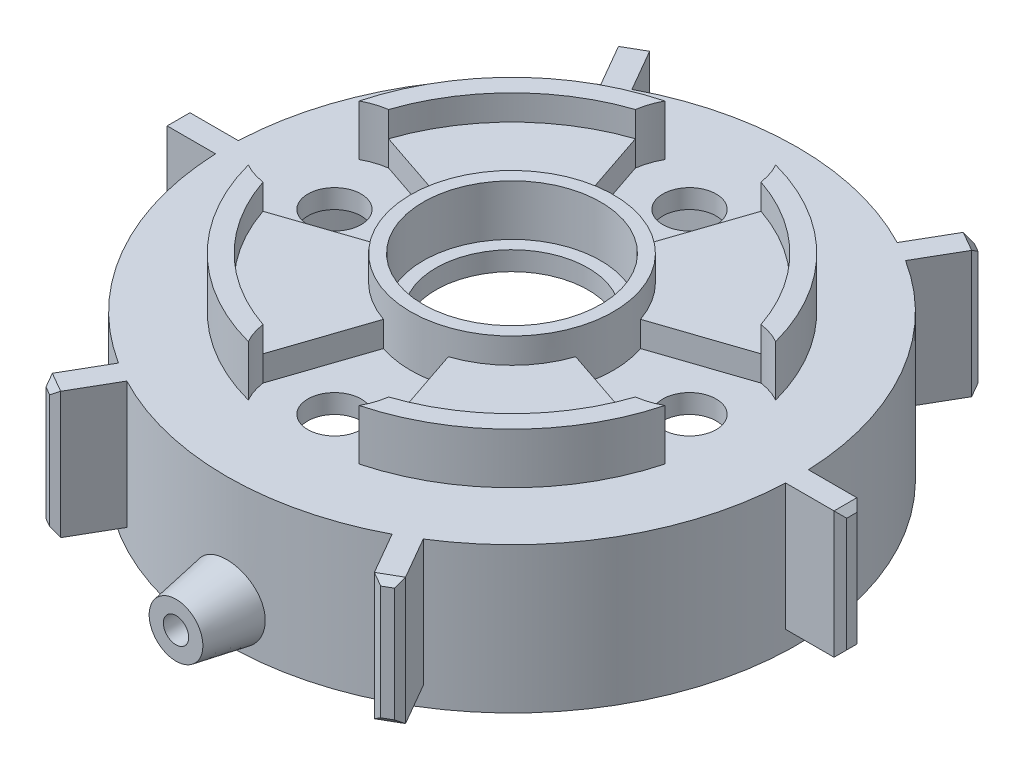
SolidWorks part; units mm, degrees
ref_plane "前视基准面" through (0, 0, 0) normal (0, 0, 1) x (1, 0, 0)
ref_plane "上视基准面" through (0, 0, 0) normal (0, 1, 0) x (1, 0, 0)
ref_plane "右视基准面" through (0, 0, 0) normal (1, 0, 0) x (0, 0, -1)
sketch "草图2" plane through (0, 0, 0) normal (0, 1, 0) x (1, 0, 0)
  line L0 (0, 30.8283) -> (0, -31.2236) construction
  line L1 (-31.2236, 0) -> (33.595, 0) construction
  circle A0 centre (0, 0) radius 22.5
  circle A1 centre (0, 0) radius 14 construction
  circle A2 centre (14, 0) radius 2.1
  circle A3 centre (0, 14) radius 2.1
  circle A4 centre (0, -14) radius 2.1
  circle A5 centre (-14, 0) radius 2.1
  circle A6 centre (0, 0) radius 6
  dimension "D1" = 45
  dimension "D2" = 4.2
  dimension "D3" = 4.2
  dimension "D4" = 28
  dimension "D5" = 12
extrude "凸台-拉伸1" add sketch "草图2" along normal blind 1.5
sketch "草图4" plane through (0, 0, 0) normal (0, -1, 0) x (1, 0, 0)
  circle A1 centre (0, 0) radius 22.5 construction
  circle A2 centre (0, 0) radius 22.5
  circle A3 centre (0, 0) radius 21
  dimension "D1" = 1.5
extrude "凸台-拉伸2" add sketch "草图4" along normal blind 10
sketch "草图5" plane through (0, 1.5, 0) normal (0, 1, 0) x (1, 0, 0)
  line L0 (-22.5, 0) -> (24.7317, 0) construction
  line L1 (0, 22.5) -> (0, -24.6712) construction
  line L2 (26.8, 0.9) -> (26.8, -0.9)
  line L3 (26.8, -0.9) -> (21, -0.9)
  line L4 (21, -0.9) -> (21, 0.9)
  line L5 (26.8, 0.9) -> (21, 0.9)
  line L6 (12.6206, -23.6595) -> (9.7206, -18.6365)
  line L7 (14.1794, -22.7595) -> (12.6206, -23.6595)
  line L8 (14.1794, -22.7595) -> (11.2794, -17.7365)
  line L9 (9.7206, -18.6365) -> (11.2794, -17.7365)
  line L10 (-14.1794, -22.7595) -> (-11.2794, -17.7365)
  line L11 (-12.6206, -23.6595) -> (-14.1794, -22.7595)
  line L12 (-12.6206, -23.6595) -> (-9.7206, -18.6365)
  line L13 (-11.2794, -17.7365) -> (-9.7206, -18.6365)
  line L14 (-26.8, 0.9) -> (-21, 0.9)
  line L15 (-26.8, -0.9) -> (-26.8, 0.9)
  line L16 (-26.8, -0.9) -> (-21, -0.9)
  line L17 (-21, 0.9) -> (-21, -0.9)
  line L18 (-12.6206, 23.6595) -> (-9.7206, 18.6365)
  line L19 (-14.1794, 22.7595) -> (-12.6206, 23.6595)
  line L20 (-14.1794, 22.7595) -> (-11.2794, 17.7365)
  line L21 (-9.7206, 18.6365) -> (-11.2794, 17.7365)
  line L22 (14.1794, 22.7595) -> (11.2794, 17.7365)
  line L23 (12.6206, 23.6595) -> (14.1794, 22.7595)
  line L24 (12.6206, 23.6595) -> (9.7206, 18.6365)
  line L25 (11.2794, 17.7365) -> (9.7206, 18.6365)
  circle A0 centre (0, 0) radius 22.5 construction
  point P14 (21, 0)
  point P15 (26.8, 0)
  dimension "D1" = 1.8
  dimension "D2" = 21
  dimension "D3" = 5.8
  dimension "D4" = 6
extrude "凸台-拉伸3" add sketch "草图5" against normal blind 10
sketch "草图6" plane through (0, 1.5, 0) normal (0, 1, 0) x (1, 0, 0)
  arc A0 (16.4286, 4.3706) -> (4.3706, 16.4286) centre (0, 0) ccw
  arc A1 (14.6875, 4.9525) -> (4.9525, 14.6875) centre (0, 0) ccw
  circle A2 centre (0, 0) radius 8
  circle A4 centre (0, 0) radius 7
  arc A7 (4.3706, -16.4286) -> (4.9525, -14.6875) centre (0, -14) ccw
  arc A8 (-14.6875, 4.9525) -> (-16.4286, 4.3706) centre (-14, 0) ccw
  arc A9 (16.4286, 4.3706) -> (14.6875, 4.9525) centre (14, 0) ccw
  arc A10 (4.9525, 14.6875) -> (4.3706, 16.4286) centre (0, 14) ccw
  arc A11 (14.6875, -4.9525) -> (16.4286, -4.3706) centre (14, 0) ccw
  arc A12 (4.3706, -16.4286) -> (16.4286, -4.3706) centre (0, 0) ccw
  arc A13 (4.9525, -14.6875) -> (14.6875, -4.9525) centre (0, 0) ccw
  arc A14 (-4.9525, -14.6875) -> (-4.3706, -16.4286) centre (0, -14) ccw
  arc A15 (-14.6875, -4.9525) -> (-4.9525, -14.6875) centre (0, 0) ccw
  arc A16 (-16.4286, -4.3706) -> (-14.6875, -4.9525) centre (-14, 0) ccw
  arc A17 (-16.4286, -4.3706) -> (-4.3706, -16.4286) centre (0, 0) ccw
  arc A18 (-4.9525, 14.6875) -> (-14.6875, 4.9525) centre (0, 0) ccw
  arc A19 (-4.3706, 16.4286) -> (-16.4286, 4.3706) centre (0, 0) ccw
  arc A20 (-4.3706, 16.4286) -> (-4.9525, 14.6875) centre (0, 14) ccw
  dimension "D1" = 16
  dimension "D2" = 1
  dimension "D3" = 31
  dimension "D4" = 1.5
  dimension "D5" = 10
  dimension "D6" = 10
  dimension "D7" = 10
  dimension "D8" = 10
extrude "凸台-拉伸4" add sketch "草图6" along normal blind 4
sketch "草图7" plane through (0, 1.5, 0) normal (0, 1, 0) x (1, 0, 0)
  line L0 (0, 22.5) -> (0, -29.8231) construction
  line L1 (29.3152, 0) -> (-30.7664, 0) construction
  line L2 (14.6875, -4.9525) -> (7.5806, -2.5561)
  line L3 (4.9525, -14.6875) -> (2.5561, -7.5806)
  line L4 (0, 0) -> (7.5806, -2.5561) construction
  line L5 (0, 0) -> (2.5561, -7.5806) construction
  line L6 (-4.9525, -14.6875) -> (-2.5561, -7.5806)
  line L7 (-14.6875, -4.9525) -> (-7.5806, -2.5561)
  line L8 (-14.6875, 4.9525) -> (-7.5806, 2.5561)
  line L9 (-4.9525, 14.6875) -> (-2.5561, 7.5806)
  line L10 (4.9525, 14.6875) -> (2.5561, 7.5806)
  line L11 (14.6875, 4.9525) -> (7.5806, 2.5561)
  arc A0 (10.4616, 19.92) -> (-10.4616, 19.92) centre (0, 0) ccw construction
  circle A1 centre (0, 0) radius 8 construction
  arc A2 (4.9525, -14.6875) -> (14.6875, -4.9525) centre (0, 0) ccw construction
  arc A4 (4.9525, -14.6875) -> (14.6875, -4.9525) centre (0, 0) ccw
  arc A5 (2.5561, -7.5806) -> (7.5806, -2.5561) centre (0, 0) ccw
  arc A6 (-2.5561, -7.5806) -> (-7.5806, -2.5561) centre (0, 0) cw
  arc A7 (-4.9525, -14.6875) -> (-14.6875, -4.9525) centre (0, 0) cw
  arc A8 (-4.9525, 14.6875) -> (-14.6875, 4.9525) centre (0, 0) ccw
  arc A9 (-2.5561, 7.5806) -> (-7.5806, 2.5561) centre (0, 0) ccw
  arc A10 (2.5561, 7.5806) -> (7.5806, 2.5561) centre (0, 0) cw
  arc A11 (4.9525, 14.6875) -> (14.6875, 4.9525) centre (0, 0) cw
extrude "凸台-拉伸5" add sketch "草图7" along normal blind 2
chamfer "倒角1" distance 0.5 angle 45 24 edges at (-12.6206, -3.5, 23.6595) (-13.4, -8.5, 23.2095) (-14.1794, -3.5, 22.7595) (-13.4, 1.5, 23.2095) (-26.8, -3.5, 0.9) (-26.8, -8.5, 0) (-26.8, -3.5, -0.9) (-26.8, 1.5, 0) (-14.1794, -3.5, -22.7595) (-13.4, -8.5, -23.2095) (-12.6206, -3.5, -23.6595) (-13.4, 1.5, -23.2095) (12.6206, -3.5, -23.6595) (13.4, -8.5, -23.2095) (14.1794, -3.5, -22.7595) (13.4, 1.5, -23.2095) (26.8, -3.5, -0.9) (26.8, -8.5, 0) (26.8, -3.5, 0.9) (26.8, 1.5, 0) (14.1794, -3.5, 22.7595) (13.4, -8.5, 23.2095) (12.6206, -3.5, 23.6595) (13.4, 1.5, 23.2095)
sketch "草图9" plane through (0, 0, 0) normal (0, 0, 1) x (1, 0, 0)
  line L0 (0, 0) -> (0, -17.9449) construction
  line L1 (-22.5, -10) -> (22.5, -10) construction
  circle A0 centre (0, -7) radius 3
  point P5 (0, -6.3685)
  dimension "D1" = 6
  dimension "D2" = 3
extrude "凸台-拉伸6" add sketch "草图9" along normal blind 5 draft 10 from offset 21.5
sketch "草图10" plane through (0, 0, 26.5) normal (0, 0, 1) x (1, 0, 0)
  circle A0 centre (0, -7) radius 1
  point P3 (0, 0)
  dimension "D1" = 2
extrude "切除-拉伸1" cut sketch "草图10" against normal blind 5
